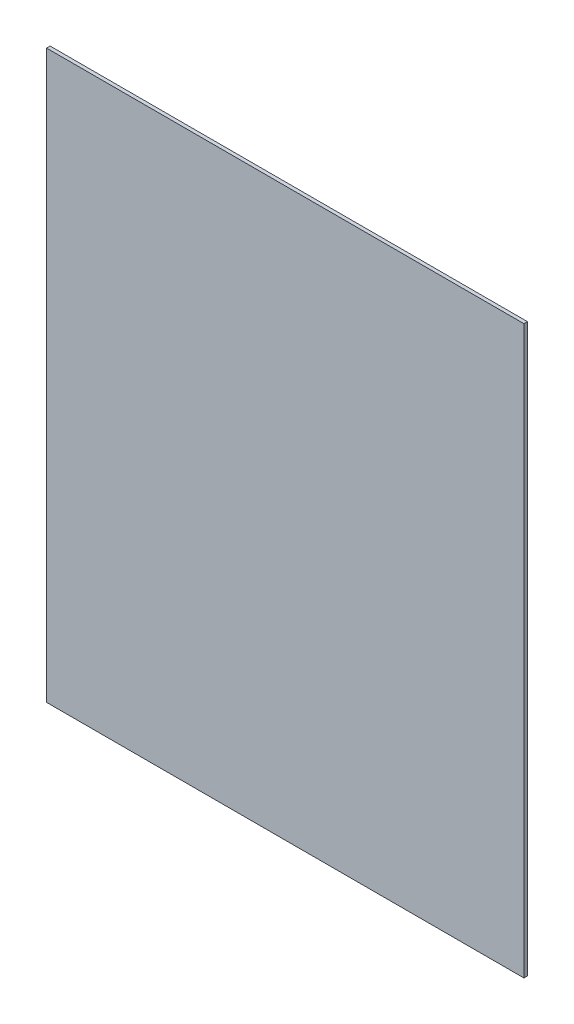
SolidWorks part; units mm, degrees
ref_plane "Front" through (0, 0, 0) normal (0, 0, 1) x (1, 0, 0)
ref_plane "Top" through (0, 0, 0) normal (0, 1, 0) x (1, 0, 0)
ref_plane "Right" through (0, 0, 0) normal (1, 0, 0) x (0, 0, -1)
sketch "Sketch1" plane through (0, 0, 0) normal (0, 0, 1) x (1, 0, 0)
  line L1 (0, 0) -> (427.99, 0)
  line L2 (0, 0) -> (0, 508)
  line L3 (0, 508) -> (427.99, 508)
  line L4 (427.99, 0) -> (427.99, 508)
  dimension "D1" = 508
  dimension "D2" = 427.99
extrude "Boss-Extrude1" add sketch "Sketch1" along normal blind 3.175
